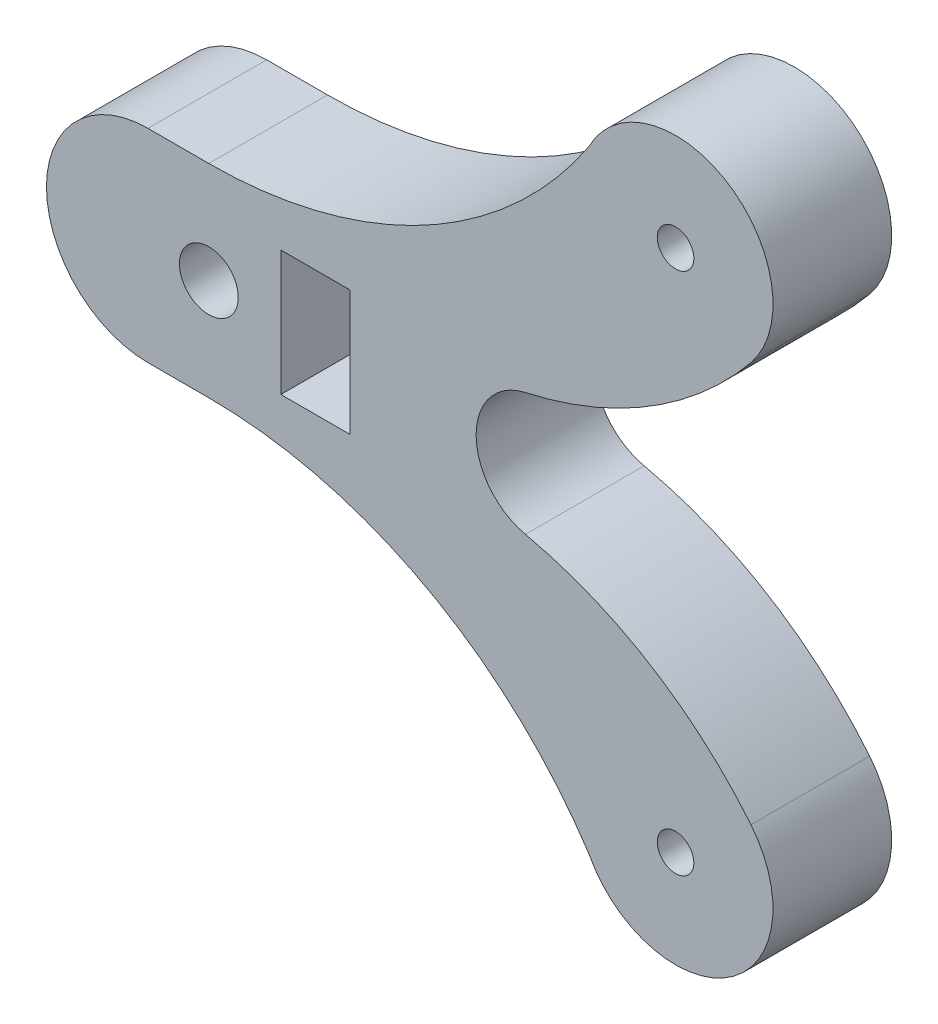
SolidWorks part; units mm, degrees
material "Acrylic (Medium-high impact)"
ref_plane "Front Plane" through (0, 0, 0) normal (0, 0, 1) x (1, 0, 0)
ref_plane "Top Plane" through (0, 0, 0) normal (0, 1, 0) x (1, 0, 0)
ref_plane "Right Plane" through (0, 0, 0) normal (1, 0, 0) x (0, 0, -1)
sketch "Sketch1" plane through (0, 0, 0) normal (0, 0, 1) x (1, 0, 0)
  line L0 (587.4699, 435.3658) -> (583.9197, 435.3658) construction
  line L1 (594.1695, 438.4483) -> (594.1695, 432.2833) construction
  line L2 (592.4695, 438.4483) -> (595.8695, 438.4483)
  line L3 (595.8695, 438.4483) -> (595.8695, 432.2833)
  line L4 (595.8695, 432.2833) -> (592.4695, 432.2833)
  line L5 (592.4695, 432.2833) -> (592.4695, 438.4483)
  line L6 (588.9197, 433.916) -> (588.9197, 430.3658) construction
  line L7 (588.9197, 436.8156) -> (588.9197, 440.3658) construction
  line L8 (592.4695, 435.3658) -> (595.8695, 435.3658) construction
  line L9 (588.9197, 440.3658) -> (585.9197, 440.3658)
  line L10 (611.9197, 448.2658) -> (611.9197, 422.4658) construction
  line L11 (611.9197, 422.4658) -> (611.9197, 427.7978) construction
  line L12 (602.0913, -566.5041) -> (602.0913, 49433.4959) construction
  line L13 (611.9197, 422.4658) -> (611.9197, 417.1338) construction
  line L14 (588.9197, 430.3658) -> (585.9197, 430.3658)
  line L16 (611.9197, 448.2658) -> (611.9197, 453.5978) construction
  line L17 (611.9197, 448.2658) -> (611.9197, 442.9338) construction
  line L20 (607.777, 435.3658) -> (50607.777, 435.3658) construction
  circle A0 centre (611.9197, 448.2658) radius 0.9
  circle A1 centre (611.9197, 422.4658) radius 0.9
  circle A2 centre (588.9197, 435.3658) radius 1.4498
  arc A3 (585.9197, 440.3658) -> (585.9197, 430.3658) centre (585.9197, 435.3658) ccw
  arc A4 (607.6499, 450.4587) -> (615.6343, 445.2258) centre (611.9197, 448.2658) cw
  arc A5 (588.9197, 440.3658) -> (607.6499, 450.4587) centre (588.9197, 462.7918) ccw
  arc A6 (604.5218, 438.3927) -> (604.5218, 432.339) centre (605.1913, 435.3658) ccw
  arc A7 (604.5218, 438.3927) -> (615.6343, 445.2258) centre (600.22, 457.841) ccw
  arc A8 (604.5218, 432.339) -> (615.6343, 425.5059) centre (600.22, 412.8906) cw
  arc A9 (607.6499, 420.2729) -> (615.6343, 425.5059) centre (611.9197, 422.4658) ccw
  arc A10 (588.9197, 430.3658) -> (607.6499, 420.2729) centre (588.9197, 407.9398) cw
  point P33 (602.0913, 435.3658)
  point P35 (590.3695, 435.3658)
  point P37 (611.9197, 453.0658)
  point P39 (611.9197, 417.6658)
  dimension "D1" = 2.1
  dimension "D4" = 1.8
  dimension "D8" = 3.1
  dimension "D10" = 4.8
  dimension "D11" = 3
  dimension "D14" = 35.4
  dimension "D2" = 23
  dimension "D3" = 10
  dimension "D5" = 12.9
  dimension "D6" = 6.165
  dimension "D7" = 3.4
  dimension "D9" = 6.2218
  dimension "D12" = 18.7302
  dimension "D13" = 11.1125
extrude "Boss-Extrude1" add sketch "Sketch1" along normal blind 5.85
